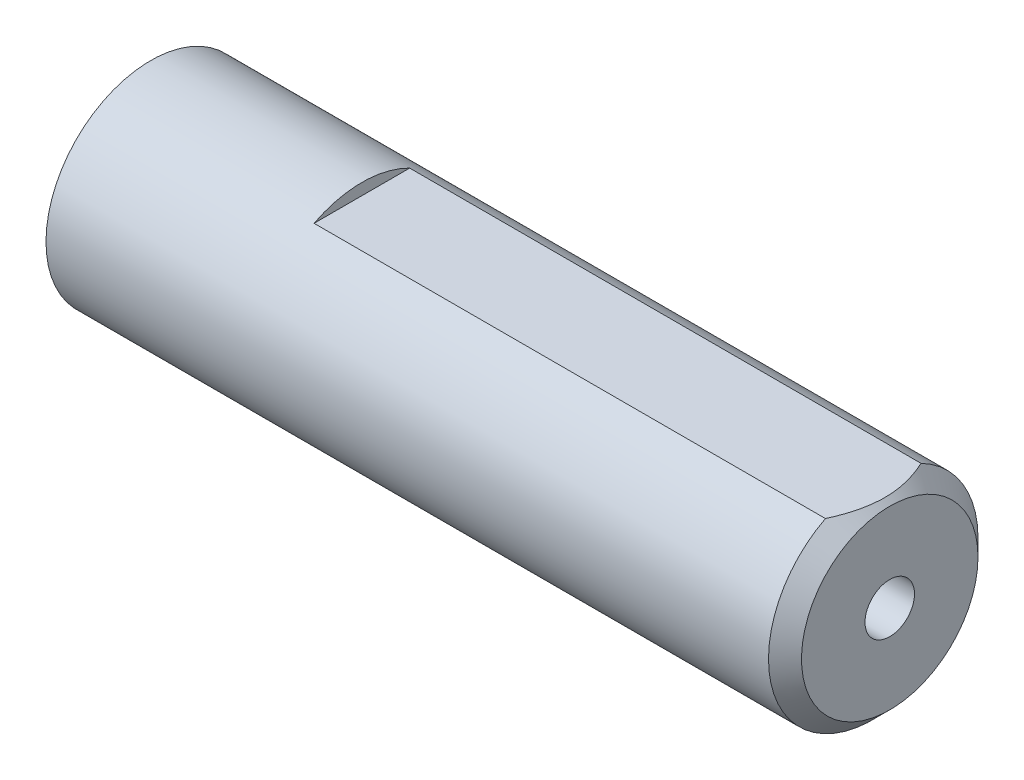
SolidWorks part; units mm, degrees
ref_plane "Plano frontal" through (0, 0, 0) normal (0, 0, 1) x (1, 0, 0)
ref_plane "Plano superior" through (0, 0, 0) normal (0, 1, 0) x (1, 0, 0)
ref_plane "Plano direito" through (0, 0, 0) normal (1, 0, 0) x (0, 0, -1)
sketch "Esboço1" plane through (0, 0, 0) normal (1, 0, 0) x (0, 0, -1)
  circle A0 centre (0, 0) radius 3.175
  dimension "D1" = 6.35
extrude "Ressalto-extrusão1" add sketch "Esboço1" along normal blind 22.4
chamfer "Chanfro1" distance 0.5 angle 45 1 edges at (22.4, 0, -3.175)
sketch "Esboço3" plane through (22.4, 0, 0) normal (1, 0, 0) x (0, 0, -1)
  line L0 (0, 2.825) -> (0, -3.175) construction
  line L2 (-1.4491, 3.175) -> (1.4491, 3.175)
  line L3 (-1.4491, 3.175) -> (-1.4491, 2.825)
  line L4 (-1.4491, 2.825) -> (1.4491, 2.825)
  line L5 (1.4491, 3.175) -> (1.4491, 2.825)
  circle A0 centre (0, 0) radius 3.175 construction
  point P8 (0, 0)
  point P9 (0, 0)
  point P12 (0, 0)
  point P14 (0, 0)
  point P15 (0, -3.175)
  point P16 (0, 0)
  point P17 (0, 0)
  dimension "D1" = 6
extrude "Corte-extrusão1" cut sketch "Esboço3" against normal blind 16
sketch "Esboço4" plane through (22.4, 0, 0) normal (1, 0, 0) x (0, 0, -1)
  circle A0 centre (0, 0) radius 0.75
  dimension "D1" = 1.5
extrude "Corte-extrusão2" cut sketch "Esboço4" against normal blind 3
